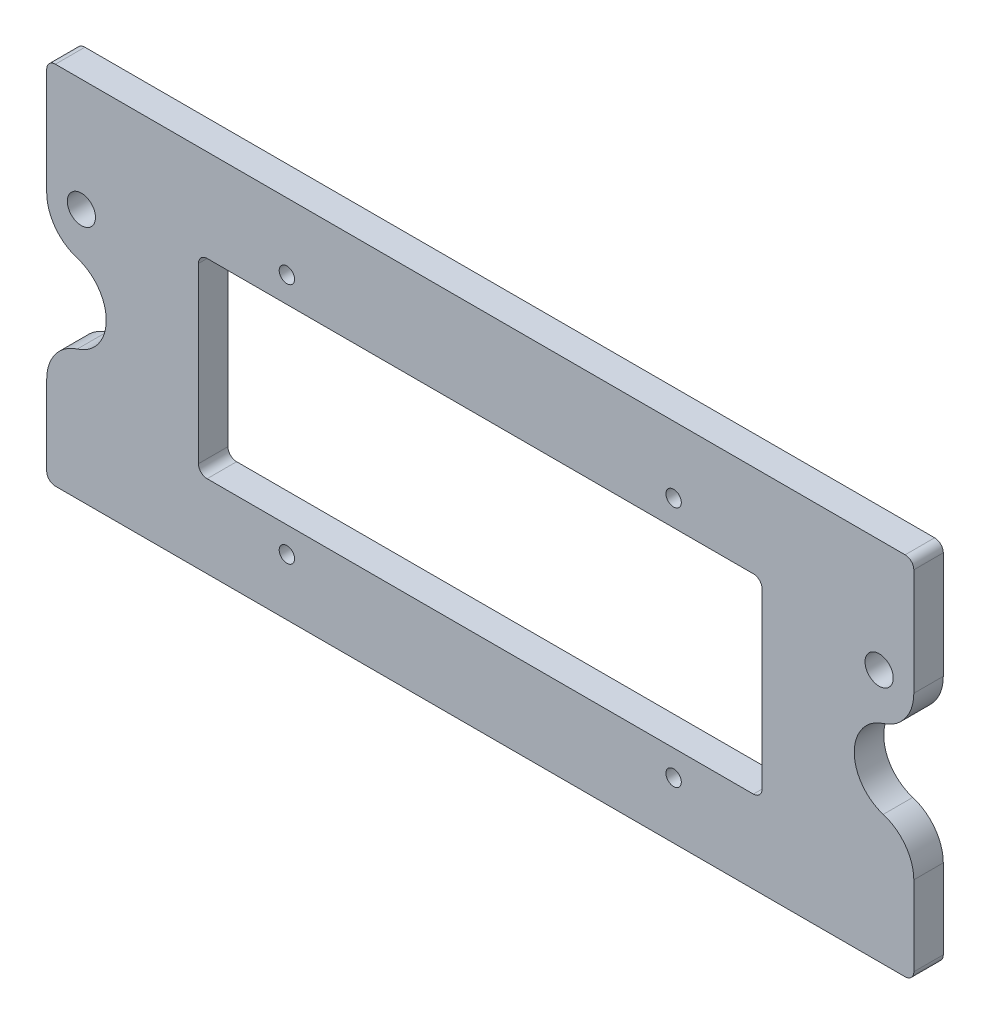
SolidWorks part; units mm, degrees
ref_plane "Front Plane" through (0, 0, 0) normal (0, 0, 1) x (1, 0, 0)
ref_plane "Top Plane" through (0, 0, 0) normal (0, 1, 0) x (1, 0, 0)
ref_plane "Right Plane" through (0, 0, 0) normal (1, 0, 0) x (0, 0, -1)
sketch "Sketch1" plane through (0, 0, 0) normal (0, 0, 1) x (1, 0, 0)
  line L1 (100, -42.15) -> (-100, -42.15)
  line L2 (100, -42.15) -> (100, 42.15)
  line L3 (100, 42.15) -> (-100, 42.15)
  line L4 (-100, -42.15) -> (-100, 42.15)
  line L5 (100, -42.15) -> (-100, 42.15) construction
  line L6 (100, 42.15) -> (-100, -42.15) construction
  point P0 (0, 0)
  dimension "D1" = 200
  dimension "D2" = 84.3
extrude "Boss-Extrude1" add sketch "Sketch1" along normal blind 6.8
sketch "Sketch2" plane through (0, 0, 6.8) normal (0, 0, 1) x (1, 0, 0)
  line L0 (100, 42.15) -> (-100, 42.15) construction
  line L1 (92, 16.15) -> (-92, 16.15) construction
  circle A0 centre (-92, 16.15) radius 3.25
  circle A1 centre (92, 16.15) radius 3.25
  point P10 (0, 16.15)
  dimension "D1" = 6.5
  dimension "D2" = 92
  dimension "D3" = 26
extrude "Cut-Extrude1" cut sketch "Sketch2" against normal blind 6.8
fillet "Fillet1" radius 2 4 edges at (100, 42.15, 3.4) (100, -42.15, 3.4) (-100, -42.15, 3.4) (-100, 42.15, 3.4)
sketch "Sketch3" plane through (0, 0, 6.8) normal (0, 0, 1) x (1, 0, 0)
  line L0 (0, 20.85) -> (0, -23.15) construction
  line L1 (-98, -42.15) -> (98, -42.15) construction
  line L3 (44.6, -29.0722) -> (-44.6, -29.0722) construction
  line L4 (44.6, -29.0722) -> (44.6, 26.7722) construction
  line L5 (44.6, 26.7722) -> (-44.6, 26.7722) construction
  line L6 (-44.6, -29.0722) -> (-44.6, 26.7722) construction
  line L7 (44.6, -29.0722) -> (-44.6, 26.7722) construction
  line L8 (44.6, 26.7722) -> (-44.6, -29.0722) construction
  line L9 (-65, -23.15) -> (65, -23.15)
  line L10 (65, -23.15) -> (65, 20.85)
  line L11 (65, 20.85) -> (-65, 20.85)
  line L12 (-65, 20.85) -> (-65, -23.15)
  circle A0 centre (-44.6, 26.7722) radius 1.775
  circle A1 centre (44.6, 26.7722) radius 1.775
  circle A2 centre (44.6, -29.0722) radius 1.775
  circle A3 centre (-44.6, -29.0722) radius 1.775
  point P4 (0, 20.85)
  point P10 (0, -1.15)
  dimension "D6" = 3.55
  dimension "D1" = 130
  dimension "D2" = 19
  dimension "D3" = 44
  dimension "D4" = 89.2
  dimension "D5" = 55.8444
extrude "Cut-Extrude2" cut sketch "Sketch3" against normal through all
fillet "Fillet2" radius 2 4 edges at (65, 20.85, 3.4) (65, -23.15, 3.4) (-65, 20.85, 3.4) (-65, -23.15, 3.4)
sketch "Sketch4" plane through (0, 0, 6.8) normal (0, 0, 1) x (1, 0, 0)
  line L0 (-79.7642, -3.15) -> (-95.7642, -3.15) construction
  line L1 (-79.7642, 9.844) -> (-79.7642, -16.144) construction
  line L2 (-95.7642, 6.35) -> (-108.8918, 6.35)
  line L3 (-108.8918, 6.35) -> (-108.8918, -12.65)
  line L4 (-108.8918, -12.65) -> (-95.7642, -12.65)
  arc A0 (-95.7642, -12.65) -> (-95.7642, 6.35) centre (-95.7642, -3.15) ccw
  dimension "D1" = 19
  dimension "D2" = 16
extrude "Cut-Extrude3" cut sketch "Sketch4" against normal blind 10
mirror "Mirror3" about plane through (0, 0, 0) normal (1, 0, 0) of "Cut-Extrude3"
fillet "Fillet3" radius 10 4 edges at (-100, -12.65, 3.4) (-100, 6.35, 3.4) (100, 6.35, 3.4) (100, -12.65, 3.4)
